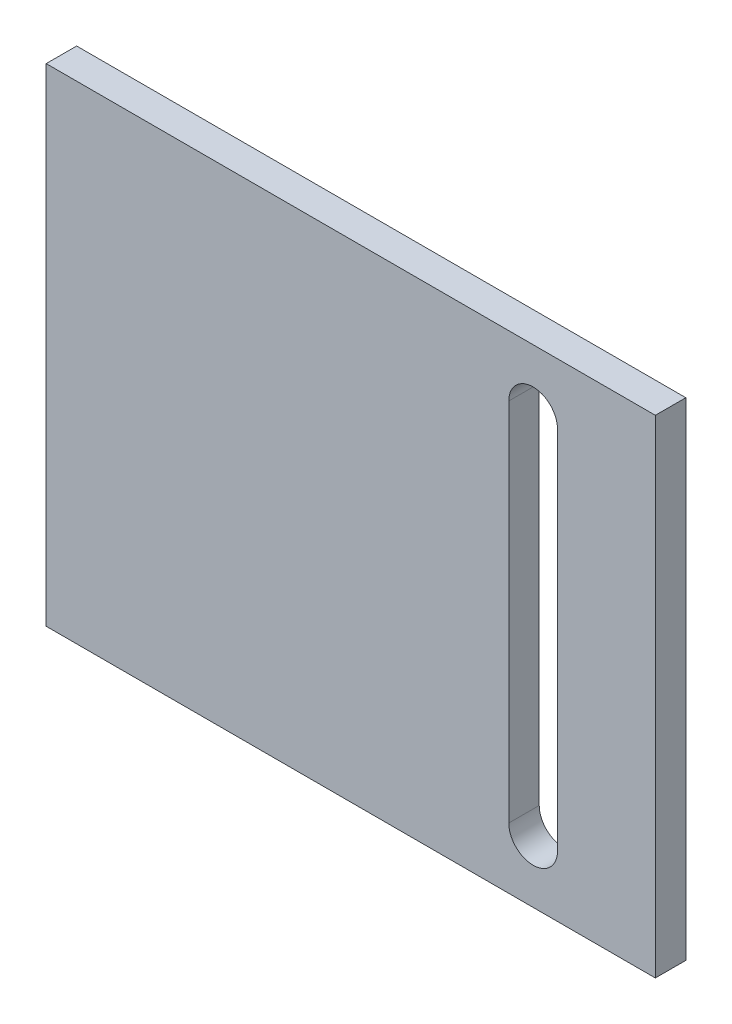
SolidWorks part; units mm, degrees
ref_plane "Front Plane" through (0, 0, 0) normal (0, 0, 1) x (1, 0, 0)
ref_plane "Top Plane" through (0, 0, 0) normal (0, 1, 0) x (1, 0, 0)
ref_plane "Right Plane" through (0, 0, 0) normal (1, 0, 0) x (0, 0, -1)
sketch "Sketch1" plane through (0, 0, 0) normal (0, 0, 1) x (1, 0, 0)
  line L0 (73.9871, 26.9936) -> (73.9871, -33.0064) construction
  line L1 (-5.9486, 36.9936) -> (94.0514, 36.9936)
  line L2 (-5.9486, 36.9936) -> (-5.9486, -43.0064)
  line L3 (-5.9486, -43.0064) -> (94.0514, -43.0064)
  line L4 (94.0514, 36.9936) -> (94.0514, -43.0064)
  line L5 (77.9871, 26.9936) -> (77.9871, -33.0064)
  line L6 (69.9871, 26.9936) -> (69.9871, -33.0064)
  arc A0 (77.9871, 26.9936) -> (69.9871, 26.9936) centre (73.9871, 26.9936) ccw
  arc A1 (69.9871, -33.0064) -> (77.9871, -33.0064) centre (73.9871, -33.0064) ccw
  point P6 (73.9871, -3.0064)
  dimension "D4" = 4
  dimension "D1" = 100
  dimension "D2" = 80
  dimension "D3" = 60
  dimension "D5" = 40
extrude "Boss-Extrude1" add sketch "Sketch1" along normal blind 5
